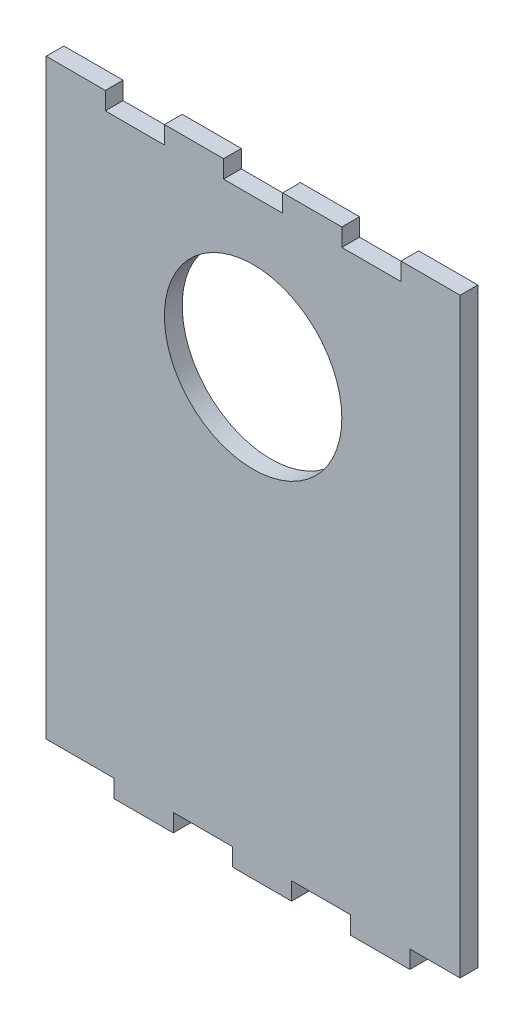
SolidWorks part; units mm, degrees
ref_plane "Front Plane" through (0, 0, 0) normal (0, 0, 1) x (1, 0, 0)
ref_plane "Top Plane" through (0, 0, 0) normal (0, 1, 0) x (1, 0, 0)
ref_plane "Right Plane" through (0, 0, 0) normal (1, 0, 0) x (0, 0, -1)
sketch "Sketch1" plane through (0, 0, 0) normal (0, 0, 1) x (1, 0, 0)
  line L1 (-35, -50) -> (35, -50)
  line L2 (-35, -50) -> (-35, 50)
  line L3 (-35, 50) -> (35, 50)
  line L4 (35, -50) -> (35, 50)
  line L5 (-35, -50) -> (35, 50) construction
  line L6 (-35, 50) -> (35, -50) construction
  line L7 (-3.5, -50) -> (6.5, -50)
  line L8 (-3.5, -50) -> (-3.5, -53)
  line L9 (-3.5, -53) -> (6.5, -53)
  line L10 (6.5, -50) -> (6.5, -53)
  line L11 (-3.5, -50) -> (6.5, -53) construction
  line L12 (-3.5, -53) -> (6.5, -50) construction
  line L13 (16.5, -50) -> (26.5, -50)
  line L14 (16.5, -50) -> (16.5, -53)
  line L15 (16.5, -53) -> (26.5, -53)
  line L16 (26.5, -50) -> (26.5, -53)
  line L17 (16.5, -50) -> (26.5, -53) construction
  line L18 (16.5, -53) -> (26.5, -50) construction
  line L19 (-13.5, -50) -> (-23.5, -50)
  line L20 (-13.5, -50) -> (-13.5, -53)
  line L21 (-13.5, -53) -> (-23.5, -53)
  line L22 (-23.5, -50) -> (-23.5, -53)
  line L23 (-13.5, -50) -> (-23.5, -53) construction
  line L24 (-13.5, -53) -> (-23.5, -50) construction
  point P0 (0, 0)
  point P10 (1.5, -51.5)
  point P15 (21.5, -51.5)
  point P20 (-18.5, -51.5)
  dimension "D1" = 10
  dimension "D2" = 10
  dimension "D3" = 10
  dimension "D4" = 3
  dimension "D5" = 3
  dimension "D6" = 3
  dimension "D7" = 10
  dimension "D8" = 10
  dimension "D9" = 70
  dimension "D10" = 100
  dimension "D11" = 11.5
extrude "Boss-Extrude1" add sketch "Sketch1" along normal blind 3 contours L1 L4 L3 L2 | L16 L1 L14 L15 | L10 L1 L8 L9 | L1 L22 L21 L20
sketch "Sketch2" plane through (0, 0, 3) normal (0, 0, 1) x (1, 0, 0)
  line L0 (-35, 50) -> (-25, 50) construction
  line L1 (-35, 50) -> (35, 50) construction
  line L3 (-25, 50) -> (-15, 50)
  line L4 (-25, 50) -> (-25, 47)
  line L5 (-25, 47) -> (-15, 47)
  line L6 (-15, 50) -> (-15, 47)
  line L7 (-25, 50) -> (-15, 47) construction
  line L8 (-25, 47) -> (-15, 50) construction
  line L9 (-5, 50) -> (5, 50)
  line L10 (-5, 50) -> (-5, 47)
  line L11 (-5, 47) -> (5, 47)
  line L12 (5, 50) -> (5, 47)
  line L13 (-5, 50) -> (5, 47) construction
  line L14 (-5, 47) -> (5, 50) construction
  line L15 (15, 50) -> (25, 50)
  line L16 (15, 50) -> (15, 47)
  line L17 (15, 47) -> (25, 47)
  line L18 (25, 50) -> (25, 47)
  line L19 (15, 50) -> (25, 47) construction
  line L20 (15, 47) -> (25, 50) construction
  point P8 (-20, 48.5)
  point P14 (0, 48.5)
  point P18 (20, 48.5)
  point P19 (15, 48.5)
  dimension "D1" = 10
  dimension "D2" = 3
  dimension "D3" = 3
  dimension "D4" = 3
  dimension "D5" = 10
  dimension "D6" = 10
  dimension "D7" = 10
  dimension "D8" = 10
extrude "Cut-Extrude1" cut sketch "Sketch2" against normal through all
sketch "Sketch3" plane through (0, 0, 3) normal (0, 0, 1) x (1, 0, 0)
  line L0 (-5, 47) -> (5, 47) construction
  circle A0 centre (0, 22) radius 15
  dimension "D2" = 30
  dimension "D1" = 25
extrude "Cut-Extrude2" cut sketch "Sketch3" against normal through all
